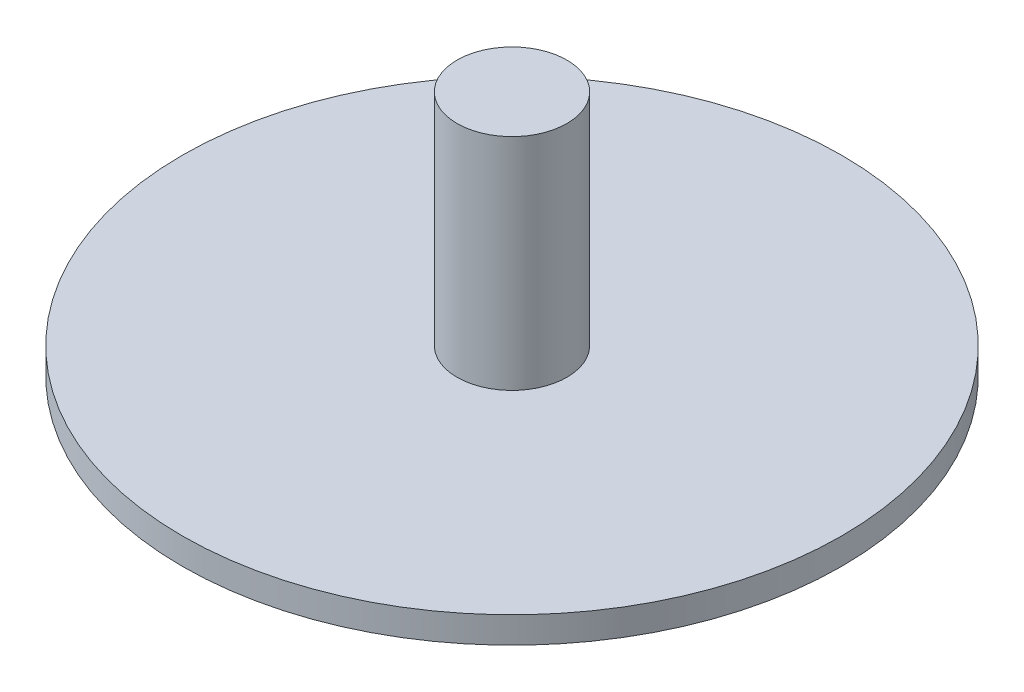
SolidWorks part; units mm, degrees
ref_plane "Front Plane" through (0, 0, 0) normal (0, 0, 1) x (1, 0, 0)
ref_plane "Top Plane" through (0, 0, 0) normal (0, 1, 0) x (1, 0, 0)
ref_plane "Right Plane" through (0, 0, 0) normal (1, 0, 0) x (0, 0, -1)
sketch "Sketch1" plane through (0, 0, 0) normal (0, 1, 0) x (1, 0, 0)
  circle A0 centre (0, 0) radius 150
  dimension "D1" = 300
extrude "Boss-Extrude1" add sketch "Sketch1" along normal blind 12
sketch "Sketch4" plane through (0, 12, 0) normal (0, 1, 0) x (1, 0, 0)
  circle A0 centre (0, 0) radius 25
  dimension "D1" = 50
extrude "Boss-Extrude2" add sketch "Sketch4" along normal blind 100
